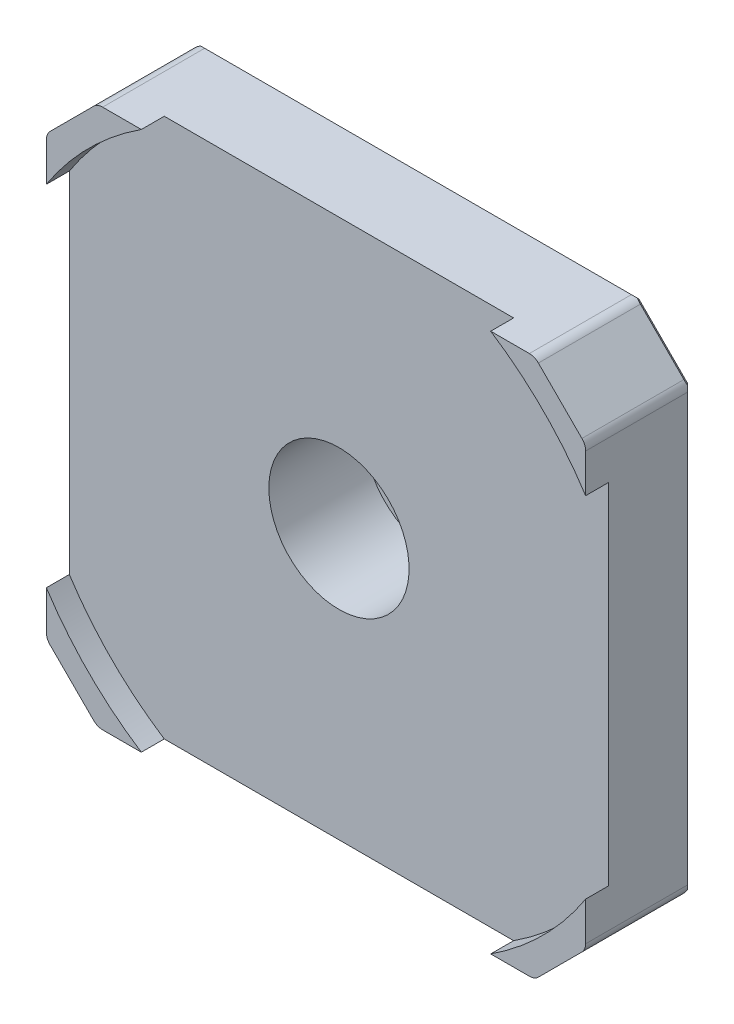
SolidWorks part; units mm, degrees
ref_plane "Alzado" through (0, 0, 0) normal (0, 0, 1) x (1, 0, 0)
ref_plane "Planta" through (0, 0, 0) normal (0, 1, 0) x (1, 0, 0)
ref_plane "Vista lateral" through (0, 0, 0) normal (1, 0, 0) x (0, 0, -1)
sketch "Croquis1" plane through (0, 0, 0) normal (0, 0, 1) x (1, 0, 0)
  line L0 (-21.15, 17.15) -> (-17.15, 21.15)
  line L1 (-17.15, 21.15) -> (17.15, 21.15)
  line L2 (-21.15, 17.15) -> (-21.15, -17.15)
  line L3 (-17.15, -21.15) -> (17.15, -21.15)
  line L4 (21.15, 17.15) -> (21.15, -17.15)
  line L5 (-21.15, 21.15) -> (21.15, -21.15) construction
  line L6 (-21.15, -21.15) -> (21.15, 21.15) construction
  line L7 (-21.15, -17.15) -> (-17.15, -21.15)
  line L8 (17.15, -21.15) -> (21.15, -17.15)
  line L9 (17.15, 21.15) -> (21.15, 17.15)
  point P0 (0, 0)
  dimension "D1" = 42.3
  dimension "D2" = 42.3
extrude "Saliente-Extruir1" add sketch "Croquis1" along normal blind 6.5
sketch "Croquis2" plane through (0, 0, 6.5) normal (0, 0, 1) x (1, 0, 0)
  line L0 (-14.15, 21.15) -> (-21.15, 14.15)
  line L1 (-14.15, 21.15) -> (14.15, 21.15)
  line L2 (-21.15, 14.15) -> (-21.15, -14.15)
  line L3 (-14.15, -21.15) -> (14.15, -21.15)
  line L4 (21.15, 14.15) -> (21.15, -14.15)
  line L5 (-21.15, 21.15) -> (21.15, -21.15) construction
  line L6 (-21.15, -21.15) -> (21.15, 21.15) construction
  line L7 (14.15, 21.15) -> (21.15, 14.15)
  line L8 (21.15, -14.15) -> (14.15, -21.15)
  line L9 (-21.15, -14.15) -> (-14.15, -21.15)
  point P0 (0, 0)
  dimension "D1" = 42.3
  dimension "D2" = 42.3
extrude "Cortar-Extruir1" [suppressed] cut sketch "Croquis2" against normal blind 2
sketch "Croquis3" plane through (0, 0, 0) normal (0, 0, -1) x (-1, 0, 0)
  circle A0 centre (0, 0) radius 11
  dimension "D1" = 22
extrude "Saliente-Extruir2" add sketch "Croquis3" along normal blind 2
sketch "Croquis4" plane through (0, 0, -2) normal (0, 0, -1) x (-1, 0, 0)
  circle A0 centre (0, 0) radius 4.5
  dimension "D1" = 9
extrude "Cortar-Extruir2" cut sketch "Croquis4" against normal blind 1
sketch "Croquis5" plane through (0, 0, -1) normal (0, 0, -1) x (-1, 0, 0)
  circle A0 centre (0, 0) radius 5.5
  dimension "D1" = 11
extrude "Cortar-Extruir3" cut sketch "Croquis5" against normal blind 10
fillet "Redondeo2" radius 0.3 8 edges at (19.15, -19.15, 0) (-19.15, -19.15, 0) (0, -21.15, 0) (-21.15, 0, 0) (-19.15, 19.15, 0) (0, 21.15, 0) (19.15, 19.15, 0) (21.15, 0, 0) profile chamfer
fillet "Redondeo3" radius 0.2 2 edges at (-4.5, 0, -2) (-11, 0, -2)
sketch "Croquis6" plane through (0, 0, 0) normal (0, 0, -1) x (-1, 0, 0)
  circle A0 centre (-15.5, 15.5) radius 1.5
  circle A1 centre (15.5, 15.5) radius 1.5
  circle A2 centre (15.5, -15.5) radius 1.5
  circle A3 centre (-15.5, -15.5) radius 1.5
  point P2 (-30.8637, 3.2123)
  point P4 (-15.5, 15.5)
  point P5 (15.5, 15.5)
  point P12 (0, 0)
  point P13 (-15.5, -15.5)
  point P14 (15.5, -15.5)
  dimension "D1" = 3
  dimension "D2" = 15.5
  dimension "D3" = 15.5
  dimension "D5" = 15.5
  dimension "D6" = 15.5
  dimension "D4" = 4
extrude "Cortar-Extruir4" [suppressed] cut sketch "Croquis6" against normal blind 4.5
fillet "Redondeo4" [suppressed] radius 0.5
hole_wizard "Отверстие обработанное метчиком M31" positions "Трехмерный эскиз1" profile "Эскиз8" tap size "M3" standard "GOST"
sketch3d "Трехмерный эскиз1"
  point P0 (15.5, 15.5, 0)
  point P3 (-15.5, 15.5, 0)
  point P6 (-15.5, -15.5, 0)
  point P9 (15.5, -15.5, 0)
sketch "Эскиз8" plane through (15.5, 15.5, 0) normal (1, 0, 0) x (0, 1, 0)
  line L0 (0, 0) -> (0, 5.7511)
  line L1 (0, 5.7511) -> (1.25, 5)
  line L2 (1.25, 5) -> (1.25, 0.55)
  line L3 (1.25, 0.55) -> (1.8, 0)
  line L5 (1.8, 0) -> (0, 0)
  line L6 (-1.25, 0.55) -> (-1.8, 0) construction
  line L10 (0, 5.7511) -> (-1.25, 5) construction
  line L11 (0, -6.35) -> (0, 107.95) construction
  dimension "Диаметр сверла" = 2.5
  dimension "Глубина сверла" = 5
  dimension "Диаметр передней зенковки" = 3.6
  dimension "Угол передней зенковки" = 90
  dimension "Угол заточки сверла" = 118
cosmetic thread "Отверстие резьбы1" parameters "D1"=4, "D2"=3
cosmetic thread "Отверстие резьбы2" parameters "D1"=4, "D2"=3
cosmetic thread "Отверстие резьбы3" parameters "D1"=4, "D2"=3
cosmetic thread "Отверстие резьбы4" parameters "D1"=4, "D2"=3
fillet "Скругление1" radius 1 8 edges at (-21.15, -17.15, 3.4) (-17.15, -21.15, 3.4) (17.15, -21.15, 3.4) (21.15, -17.15, 3.4) (-21.15, 17.15, 3.4) (-17.15, 21.15, 3.4) (21.15, 17.15, 3.4) (17.15, 21.15, 3.4)
sketch "Эскиз9" plane through (0, 0, 6.5) normal (0, 0, 1) x (1, 0, 0)
  line L0 (-21.15, -13.701) -> (-21.15, -16.7358)
  line L1 (-13.701, 21.15) -> (-16.7358, 21.15)
  line L2 (21.15, 13.701) -> (21.15, 16.7358)
  line L3 (13.701, -21.15) -> (16.7358, -21.15)
  line L8 (-21.15, 16.7358) -> (-21.15, -16.7358)
  line L9 (-20.8571, -17.4429) -> (-17.4429, -20.8571)
  line L10 (-16.7358, -21.15) -> (16.7358, -21.15)
  line L11 (17.4429, -20.8571) -> (20.8571, -17.4429)
  line L12 (21.15, -16.7358) -> (21.15, 16.7358)
  line L13 (20.8571, 17.4429) -> (17.4429, 20.8571)
  line L14 (16.7358, 21.15) -> (-16.7358, 21.15)
  line L15 (-17.4429, 20.8571) -> (-20.8571, 17.4429)
  line L16 (-21.15, 16.7358) -> (-21.15, 13.701)
  line L17 (-20.8571, -17.4429) -> (-17.4429, -20.8571)
  line L18 (-16.7358, -21.15) -> (-13.701, -21.15)
  line L19 (17.4429, -20.8571) -> (20.8571, -17.4429)
  line L20 (21.15, -16.7358) -> (21.15, -13.701)
  line L21 (20.8571, 17.4429) -> (17.4429, 20.8571)
  line L22 (16.7358, 21.15) -> (13.701, 21.15)
  line L23 (-17.4429, 20.8571) -> (-20.8571, 17.4429)
  arc A0 (-21.15, -13.701) -> (-13.701, -21.15) centre (0, 0) ccw
  arc A1 (-13.701, 21.15) -> (-21.15, 13.701) centre (0, 0) ccw
  arc A2 (21.15, 13.701) -> (13.701, 21.15) centre (0, 0) ccw
  arc A3 (13.701, -21.15) -> (21.15, -13.701) centre (0, 0) ccw
  arc A9 (-21.15, -16.7358) -> (-20.8571, -17.4429) centre (-20.15, -16.7358) ccw
  arc A10 (-17.4429, -20.8571) -> (-16.7358, -21.15) centre (-16.7358, -20.15) ccw
  arc A11 (16.7358, -21.15) -> (17.4429, -20.8571) centre (16.7358, -20.15) ccw
  arc A12 (20.8571, -17.4429) -> (21.15, -16.7358) centre (20.15, -16.7358) ccw
  arc A13 (21.15, 16.7358) -> (20.8571, 17.4429) centre (20.15, 16.7358) ccw
  arc A14 (17.4429, 20.8571) -> (16.7358, 21.15) centre (16.7358, 20.15) ccw
  arc A15 (-16.7358, 21.15) -> (-17.4429, 20.8571) centre (-16.7358, 20.15) ccw
  arc A16 (-20.8571, 17.4429) -> (-21.15, 16.7358) centre (-20.15, 16.7358) ccw
  arc A17 (-21.15, -16.7358) -> (-20.8571, -17.4429) centre (-20.15, -16.7358) ccw
  arc A18 (-17.4429, -20.8571) -> (-16.7358, -21.15) centre (-16.7358, -20.15) ccw
  arc A19 (16.7358, -21.15) -> (17.4429, -20.8571) centre (16.7358, -20.15) ccw
  arc A20 (20.8571, -17.4429) -> (21.15, -16.7358) centre (20.15, -16.7358) ccw
  arc A21 (21.15, 16.7358) -> (20.8571, 17.4429) centre (20.15, 16.7358) ccw
  arc A22 (17.4429, 20.8571) -> (16.7358, 21.15) centre (16.7358, 20.15) ccw
  arc A23 (-16.7358, 21.15) -> (-17.4429, 20.8571) centre (-16.7358, 20.15) ccw
  arc A24 (-20.8571, 17.4429) -> (-21.15, 16.7358) centre (-20.15, 16.7358) ccw
  dimension "D1" = 50.4
  dimension "D2" = 0
extrude "Бобышка-Вытянуть1" add sketch "Эскиз9" along normal offset from surface (1.8 mm away) 8.3 up to face at (13.7, 15.5, 0)
